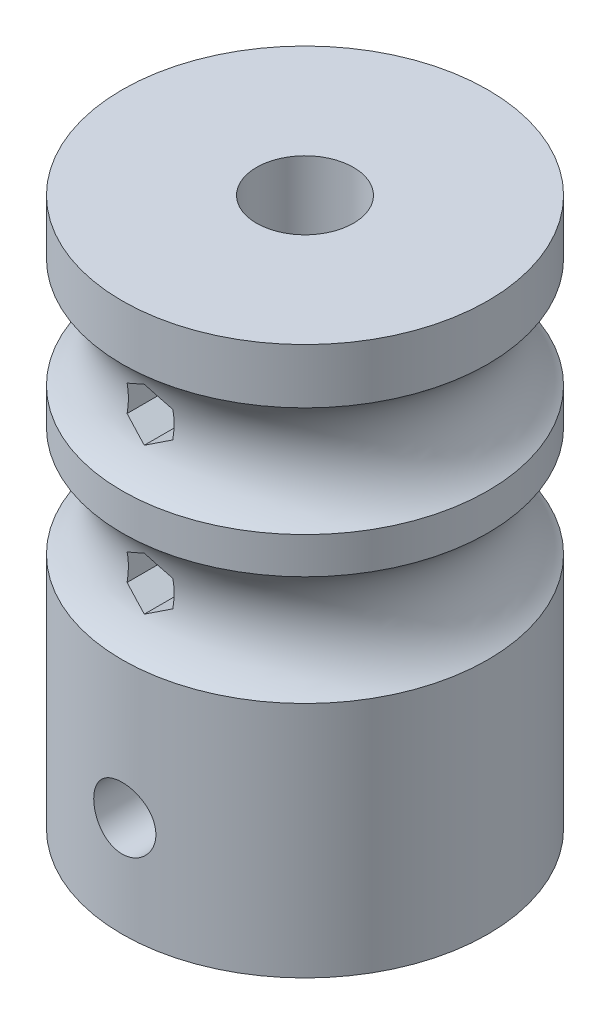
SolidWorks part; units mm, degrees
ref_plane "Alzado" through (0, 0, 0) normal (0, 0, 1) x (1, 0, 0)
ref_plane "Planta" through (0, 0, 0) normal (0, 1, 0) x (1, 0, 0)
ref_plane "Vista lateral" through (0, 0, 0) normal (1, 0, 0) x (0, 0, -1)
sketch "Croquis1" plane through (0, 0, 0) normal (0, 1, 0) x (1, 0, 0)
  circle A0 centre (0, 0) radius 10
  circle A1 centre (0, 0) radius 2.65
  dimension "D1" = 20
  dimension "D2" = 5.3
extrude "Saliente-Extruir1" add sketch "Croquis1" along normal blind 30
sketch "Croquis2" plane through (0, 0, 0) normal (0, 0, 1) x (1, 0, 0)
  circle A0 centre (0, 5.5) radius 1.7
  dimension "D2" = 3.4
  dimension "D1" = 5.5
extrude "Cortar-Extruir1" cut sketch "Croquis2" along normal blind 30
sketch "Croquis3" plane through (0, 0, 0) normal (0, -1, 0) x (-1, 0, 0)
  line L1 (3, -4) -> (-3, -4)
  line L2 (3, -4) -> (3, -7)
  line L3 (3, -7) -> (-3, -7)
  line L4 (-3, -4) -> (-3, -7)
  point P4 (0, -4)
  point P6 (0, 0)
  dimension "D1" = 6
  dimension "D2" = 3
  dimension "D3" = 4
extrude "Cortar-Extruir2" cut sketch "Croquis3" against normal blind 9
sketch "Croquis4" plane through (0, 0, 0) normal (0, 0, 1) x (1, 0, 0)
  line L0 (3, 0) -> (-3, 0) construction
  line L1 (0, 17.4434) -> (-1.25, 16.7217)
  line L2 (-1.25, 16.7217) -> (-1.25, 15.2783)
  line L3 (-1.25, 15.2783) -> (0, 14.5566)
  line L4 (0, 14.5566) -> (1.25, 15.2783)
  line L5 (1.25, 15.2783) -> (1.25, 16.7217)
  line L6 (1.25, 16.7217) -> (0, 17.4434)
  line L8 (0, 25.4434) -> (-1.25, 24.7217)
  line L9 (-1.25, 24.7217) -> (-1.25, 23.2783)
  line L10 (-1.25, 23.2783) -> (0, 22.5566)
  line L11 (0, 22.5566) -> (1.25, 23.2783)
  line L12 (1.25, 23.2783) -> (1.25, 24.7217)
  line L13 (1.25, 24.7217) -> (0, 25.4434)
  circle A0 centre (0, 16) radius 1.25 construction
  circle A1 centre (0, 24) radius 1.25 construction
  point P1 (0, 0)
  point P10 (1.2523, 24.7177)
  point P11 (0, 0)
  point P14 (0, 0)
  dimension "D1" = 2.5
  dimension "D2" = 16
  dimension "D3" = 8
extrude "Cortar-Extruir3" cut sketch "Croquis4" against normal through all both and the other way through all
sketch "Croquis5" plane through (0, 0, 0) normal (0, 0, 1) x (1, 0, 0)
  line L0 (1.25, 24.7217) -> (-1.25, 23.2783) construction
  line L1 (0, 16) -> (-10, 16) construction
  line L2 (-1.25, 16.7217) -> (1.25, 15.2783) construction
  line L3 (-10, 30) -> (-10, 0) construction
  line L4 (-8.5, 24) -> (-8.5, 16) construction
  line L5 (-10, 27) -> (-10, 21)
  line L6 (-10, 24) -> (0, 24) construction
  line L7 (0, 16) -> (0, 24) construction
  line L8 (-10, 19) -> (-10, 13)
  line L9 (-10, 13) -> (-10.0496, 12.8619)
  circle A0 centre (-10, 16) radius 3 construction
  circle A1 centre (-10, 24) radius 3 construction
  arc A2 (-10, 13) -> (-10, 19) centre (-12.25, 16) ccw
  arc A3 (-10, 27) -> (-10, 21) centre (-12.25, 24) cw
  point P4 (0, 24)
  point P11 (0, 16)
  dimension "D1" = 6
  dimension "D2" = 1.5
revolve "Cortar-Revolución1" cut sketch "Croquis5" angle 360 about L7
